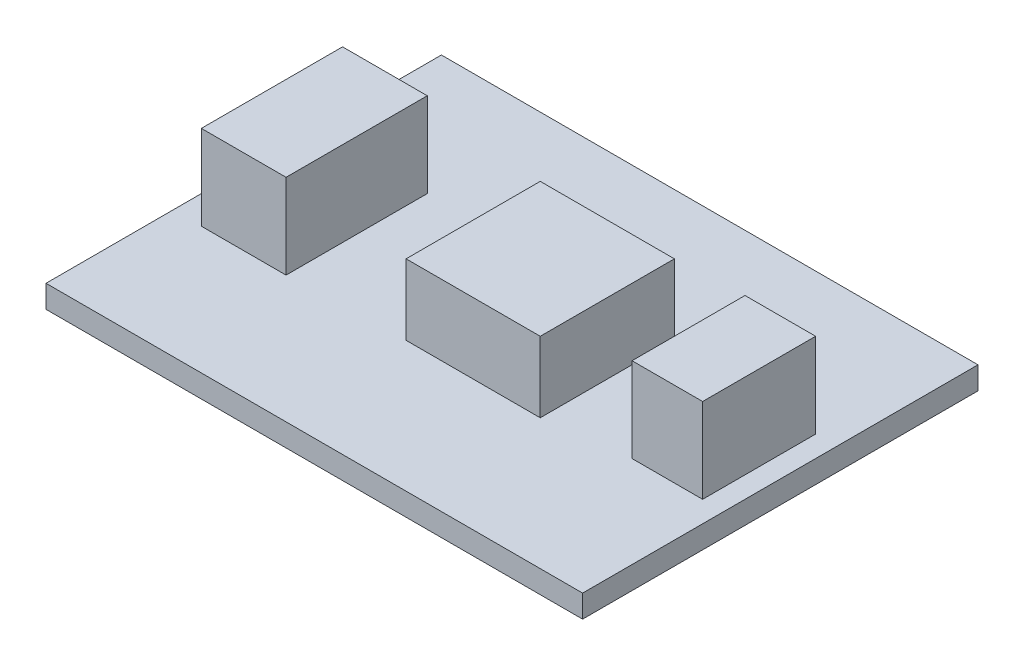
SolidWorks part; units mm, degrees
ref_plane "Front Plane" through (0, 0, 0) normal (0, 0, 1) x (1, 0, 0)
ref_plane "Top Plane" through (0, 0, 0) normal (0, 1, 0) x (1, 0, 0)
ref_plane "Right Plane" through (0, 0, 0) normal (1, 0, 0) x (0, 0, -1)
other "Configuration Table"
sketch "Sketch1" plane through (0, 0, 0) normal (0, 1, 0) x (1, 0, 0)
  line L1 (-19, -14) -> (19, -14)
  line L2 (-19, -14) -> (-19, 14)
  line L3 (-19, 14) -> (19, 14)
  line L4 (19, -14) -> (19, 14)
  line L5 (-19, -14) -> (19, 14) construction
  line L6 (-19, 14) -> (19, -14) construction
  point P6 (0, 0)
  dimension "D1" = 38
  dimension "D2" = 28
extrude "Board" add sketch "Sketch1" along normal blind 1.6
sketch "Sketch2" plane through (0, 0, 0) normal (0, 1, 0) x (1, 0, 0)
  line L0 (-17, -5) -> (-11, -5)
  line L1 (-11, -5) -> (-11, 5)
  line L2 (-11, 5) -> (-17, 5)
  line L3 (-17, 5) -> (-17, -5)
extrude "Probe_Connector" add sketch "Sketch2" along normal blind 6 from offset 1.6
sketch "Sketch3" plane through (0, 0, 0) normal (0, 1, 0) x (1, 0, 0)
  line L0 (12.5, -4) -> (17.5, -4)
  line L1 (17.5, -4) -> (17.5, 4)
  line L2 (17.5, 4) -> (12.5, 4)
  line L3 (12.5, 4) -> (12.5, -4)
extrude "Signal_Header" add sketch "Sketch3" along normal blind 6 from offset 1.6
sketch "Sketch4" plane through (0, 0, 0) normal (0, 1, 0) x (1, 0, 0)
  line L0 (-2.75, -4.75) -> (6.75, -4.75)
  line L1 (6.75, -4.75) -> (6.75, 4.75)
  line L2 (6.75, 4.75) -> (-2.75, 4.75)
  line L3 (-2.75, 4.75) -> (-2.75, -4.75)
extrude "Trim_Pot" add sketch "Sketch4" along normal blind 5 from offset 1.6
equation "\"Jar_OD\"= 90  'ASSUMED - Part G fallback - jar outer diameter"
equation "\"Jar_H\"= 120  'ASSUMED - Part G fallback - jar height"
equation "\"Pump_L\"= 45  'ASSUMED - Part G fallback"
equation "\"Pump_W\"= 24  'ASSUMED - Part G fallback"
equation "\"Pump_H\"= 33  'ASSUMED - Part G fallback"
equation "\"Pump_Outlet_OD\"= 7.5  'ASSUMED - Part G fallback"
equation "\"Tube_OD\"= 8  'ASSUMED - Part G fallback"
equation "\"Tube_ID\"= 6  'ASSUMED - Part G fallback"
equation "\"TDS_Body_Dia\"= 12  'ASSUMED - Part G fallback"
equation "\"TDS_Wet_Len\"= 45  'ASSUMED - Part G fallback - length in water"
equation "\"DS_Tube_Dia\"= 6  'ASSUMED - Part G fallback"
equation "\"DS_Tube_Len\"= 50  'ASSUMED - Part G fallback"
equation "\"ORP_Body_Dia\"= 12  'ASSUMED - Part G fallback"
equation "\"ORP_Body_Len\"= 150  'ASSUMED - Part G fallback"
equation "\"ORP_Cap_Dia\"= 16  'ASSUMED - Part G fallback"
equation "\"Turb_W\"= 33  'ASSUMED - Part G fallback - head width"
equation "\"Turb_D\"= 28  'ASSUMED - Part G fallback - head depth"
equation "\"Turb_H\"= 30  'ASSUMED - Part G fallback - head height"
equation "\"Turb_Slot_W\"= 10  'ASSUMED - Part G fallback - slot width"
equation "\"Flow_L\"= 62  'ASSUMED - Part G fallback YF-S201"
equation "\"Flow_W\"= 36  'ASSUMED - Part G fallback"
equation "\"Flow_H\"= 35  'ASSUMED - Part G fallback"
equation "\"Thread_G12_OD\"= 20.955  'ASSUMED - Part G fallback thread G1/2 (major diameter)"
equation "\"Valve_L\"= 75  'ASSUMED - Part G fallback"
equation "\"Valve_W\"= 45  'ASSUMED - Part G fallback"
equation "\"Valve_H\"= 60  'ASSUMED - Part G fallback"
equation "\"Tee_L\"= 40  'ASSUMED - Part G fallback - overall length"
equation "\"Tee_Branch_L\"= 25  'ASSUMED - Part G fallback"
equation "\"Tee_OD\"= 12  'ASSUMED - Part G fallback"
equation "\"Cuv_W\"= 12.5  'ASSUMED - old R3 cuvette (station suppressed in SS4)"
equation "\"Cuv_D\"= 12.5  'ASSUMED - old R3 cuvette (station suppressed in SS4)"
equation "\"Cuv_H\"= 45  'ASSUMED - old R3 cuvette (station suppressed in SS4)"
equation "\"LED_Board_L\"= 20  'ASSUMED - Part G fallback"
equation "\"LED_Board_W\"= 20  'ASSUMED - Part G fallback - LED at centre"
equation "\"GUVA_L\"= 20  'ASSUMED - Part G fallback"
equation "\"GUVA_W\"= 12  'ASSUMED - Part G fallback - sensor at centre"
equation "\"Reed_L\"= 27  'ASSUMED - Part G fallback MC-38 half"
equation "\"Reed_W\"= 14  'ASSUMED - Part G fallback"
equation "\"Reed_H\"= 8  'ASSUMED - Part G fallback"
equation "\"ESP_L\"= 51  'ASSUMED - Part G fallback"
equation "\"ESP_W\"= 28  'ASSUMED - Part G fallback"
equation "\"TFT_L\"= 58  'ASSUMED - Part G fallback - board"
equation "\"TFT_W\"= 35  'ASSUMED - Part G fallback - board"
equation "\"TFT_Win_L\"= 35  'ASSUMED - Part G fallback - visible window"
equation "\"TFT_Win_W\"= 28  'ASSUMED - Part G fallback - visible window"
equation "\"Relay_L\"= 50  'ASSUMED - Part G fallback"
equation "\"Relay_W\"= 26  'ASSUMED - Part G fallback"
equation "\"Relay_H\"= 19  'ASSUMED - Part G fallback"
equation "\"Mosfet_L\"= 34  'ASSUMED - Part G fallback"
equation "\"Mosfet_W\"= 17  'ASSUMED - Part G fallback"
equation "\"Mosfet_H\"= 12  'ASSUMED - Part G fallback"
equation "\"TDS_Board_L\"= 42  'ASSUMED - Part G fallback"
equation "\"TDS_Board_W\"= 32  'ASSUMED - Part G fallback"
equation "\"Turb_Board_L\"= 38  'ASSUMED - Part G fallback"
equation "\"Turb_Board_W\"= 28  'ASSUMED - Part G fallback"
equation "\"BNC_Thread_Dia\"= 9.5  'ASSUMED - Part G fallback"
equation "\"Plate_L\"= 420  'ASSUMED - Part G fallback"
equation "\"Plate_W\"= 297  'ASSUMED - Part G fallback"
equation "\"Plate_T\"= 6  'ASSUMED - Part G fallback"
equation "\"Probe_Clr\"= 0.3  'DESIGN VALUE - Part C rule 3 - printed probe hole = diameter + 0.3"
equation "\"Cuv_Clr\"= 0.2  'DESIGN VALUE - Part C rule 3 - cuvette pocket = size + 0.2"
equation "\"Label_H\"= 0.6  'DESIGN VALUE - Part D - raised label height"
equation "\"D1@Sketch1\" = \"Turb_Board_L\""
equation "\"D2@Sketch1\" = \"Turb_Board_W\""
equation "\"Booster_L\"= 150  'ASSUMED - Part G fallback - booster pump"
equation "\"Booster_W\"= 95  'ASSUMED - Part G fallback"
equation "\"Booster_H\"= 100  'ASSUMED - Part G fallback"
equation "\"PTube_OD\"= 6.35  'ASSUMED - Part G fallback - product tube 1/4 inch"
equation "\"Qz_Out\"= 12  'ASSUMED - Part G fallback - quartz channel outside square"
equation "\"Qz_Path\"= 10  'ASSUMED - Part G fallback - quartz channel inside light path"
equation "\"Qz_L\"= 40  'ASSUMED - Part G fallback - quartz channel length"
equation "\"LED860_Dia\"= 5  'ASSUMED - Part G fallback - 860 nm LED"
equation "\"BPW_L\"= 5.4  'ASSUMED - Part G fallback - BPW34"
equation "\"BPW_W\"= 4.3  'ASSUMED - Part G fallback - BPW34"
equation "\"Cart_Dia\"= 50  'ASSUMED - Part G fallback - sediment and pre-carbon cartridges"
equation "\"Cart_L\"= 255  'ASSUMED - Part G fallback"
equation "\"UF_Dia\"= 50  'ASSUMED - Part G fallback - UF cartridge"
equation "\"UF_L\"= 260  'ASSUMED - Part G fallback"
equation "\"RO_Dia\"= 62  'ASSUMED - Part G fallback - RO membrane housing"
equation "\"RO_L\"= 300  'ASSUMED - Part G fallback"
equation "\"UVC_Dia\"= 40  'ASSUMED - Part G fallback - UV-C chamber"
equation "\"UVC_L\"= 300  'ASSUMED - Part G fallback"
equation "\"Tank_W\"= 260  'ASSUMED - Part G fallback - storage tank"
equation "\"Tank_D\"= 160  'ASSUMED - Part G fallback"
equation "\"Tank_H\"= 300  'ASSUMED - Part G fallback"
equation "\"Cab_W\"= 400  'ASSUMED - Part G fallback - purifier cabinet"
equation "\"Cab_D\"= 270  'ASSUMED - Part G fallback"
equation "\"Cab_H\"= 560  'ASSUMED - Part G fallback"
equation "\"ORP_Board_L\"= 40  'ASSUMED - Part G fallback - ORP buffer board"
equation "\"ORP_Board_W\"= 30  'ASSUMED - Part G fallback"
equation "\"Opt_Board_L\"= 50  'ASSUMED - Part G fallback - optical front-end board"
equation "\"Opt_Board_W\"= 40  'ASSUMED - Part G fallback"
equation "\"Buck_L\"= 43  'ASSUMED - Part G fallback - 12 V to 5 V buck module"
equation "\"Buck_W\"= 21  'ASSUMED - Part G fallback"
equation "\"Buck_H\"= 14  'ASSUMED - Part G fallback"
equation "\"BB_L\"= 165  'ASSUMED - Part G fallback - breadboard (As_Built_R3 only)"
equation "\"BB_W\"= 55  'ASSUMED - Part G fallback"
equation "\"BB_H\"= 10  'ASSUMED - Part G fallback"
